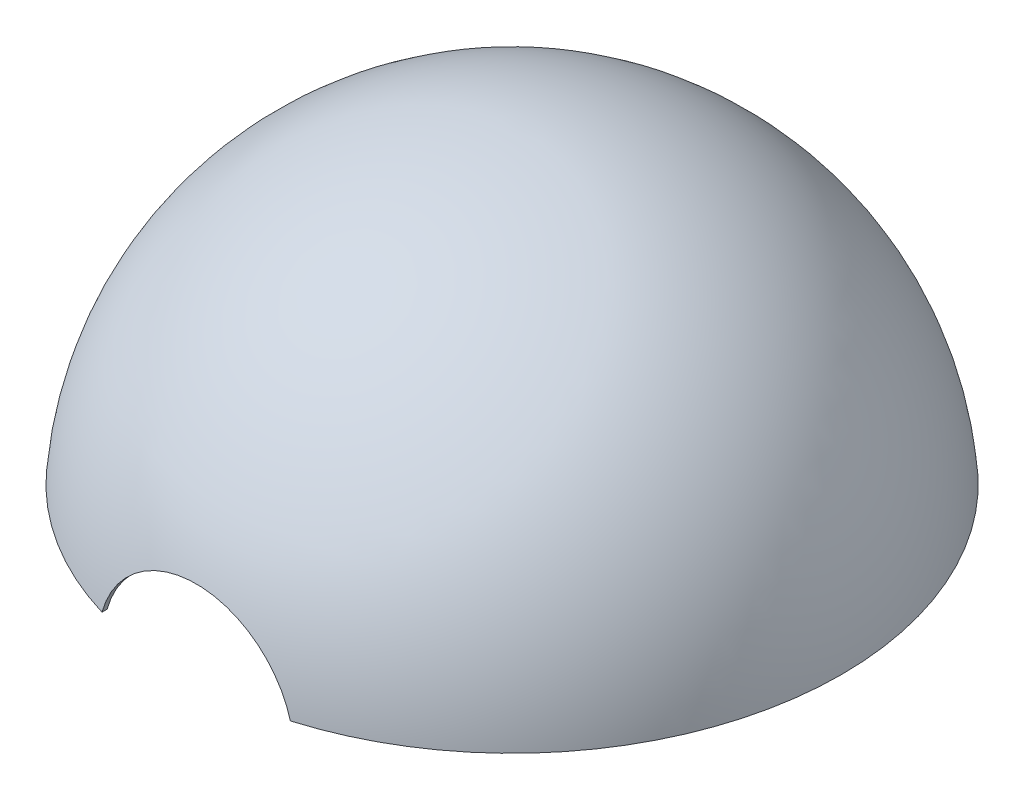
SolidWorks part; units mm, degrees
ref_plane "Front Plane" through (0, 0, 0) normal (0, 0, 1) x (1, 0, 0)
ref_plane "Top Plane" through (0, 0, 0) normal (0, 1, 0) x (1, 0, 0)
ref_plane "Right Plane" through (0, 0, 0) normal (1, 0, 0) x (0, 0, -1)
sketch "Sketch1" plane through (0, 0, 0) normal (0, 0, 1) x (1, 0, 0)
  line L0 (0, 25) -> (0, 25.375)
  line L2 (24.9199, 2) -> (25.2961, 2)
  arc A0 (25.2961, 2) -> (0, 25.375) centre (0, 0) ccw
  arc A1 (24.9199, 2) -> (0, 25) centre (0, 0) ccw
  dimension "D1" = 50.75
  dimension "D2" = 50
  dimension "D3" = 2
revolve "Revolve1" add sketch "Sketch1" angle 360 about L0
sketch "Sketch2" plane through (0, 0, 0) normal (0, 0, 1) x (1, 0, 0)
  circle A0 centre (0, 0) radius 7.5
  dimension "D1" = 15
extrude "Cut-Extrude1" cut sketch "Sketch2" along normal through all
